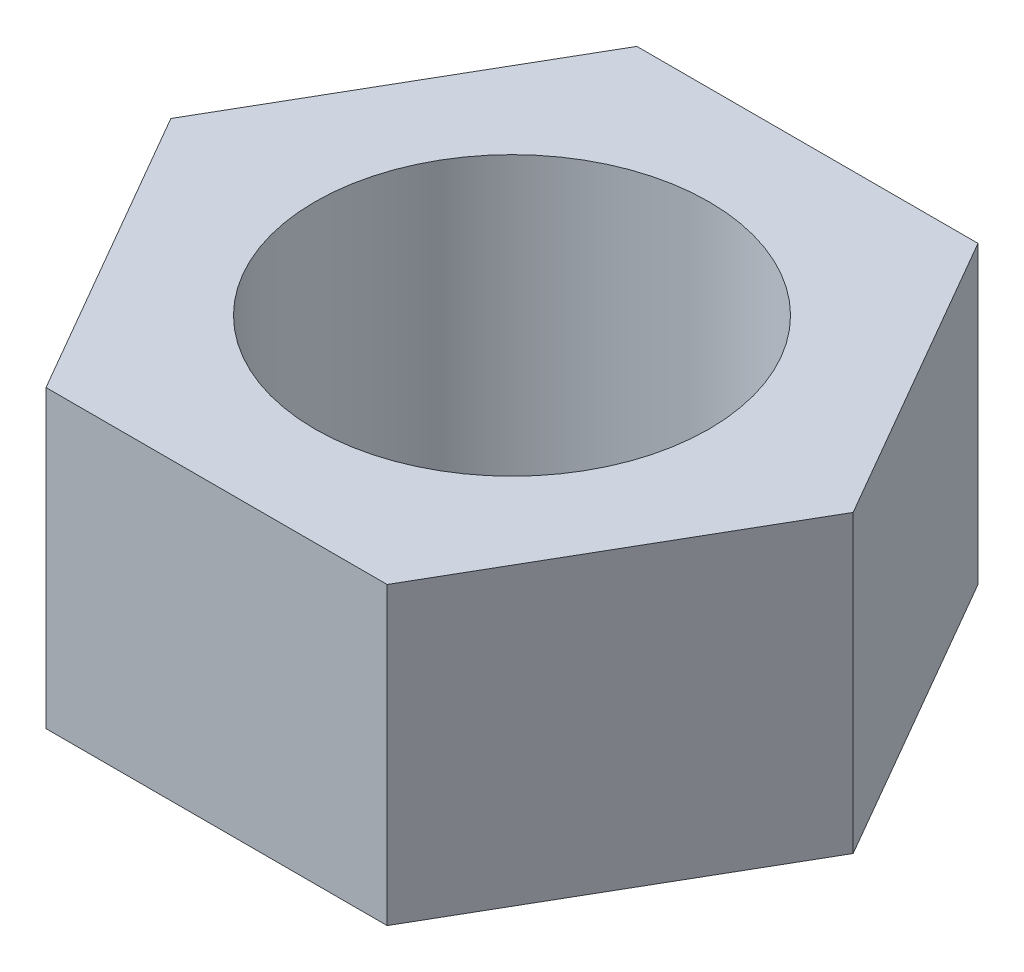
SolidWorks part; units mm, degrees
ref_plane "Front Plane" through (0, 0, 0) normal (0, 0, 1) x (1, 0, 0)
ref_plane "Top Plane" through (0, 0, 0) normal (0, 1, 0) x (1, 0, 0)
ref_plane "Right Plane" through (0, 0, 0) normal (1, 0, 0) x (0, 0, -1)
sketch "Sketch1" plane through (0, 0, 0) normal (0, 1, 0) x (1, 0, 0)
  line L1 (-1.7321, 0) -> (-0.866, -1.5)
  line L2 (-0.866, -1.5) -> (0.866, -1.5)
  line L3 (0.866, -1.5) -> (1.7321, 0)
  line L4 (1.7321, 0) -> (0.866, 1.5)
  line L5 (0.866, 1.5) -> (-0.866, 1.5)
  line L6 (-0.866, 1.5) -> (-1.7321, 0)
  circle A0 centre (0, 0) radius 1.5 construction
  circle A1 centre (0, 0) radius 1
  dimension "D1" = 2
  dimension "D2" = 3
extrude "Boss-Extrude1" add sketch "Sketch1" along normal blind 1.5
